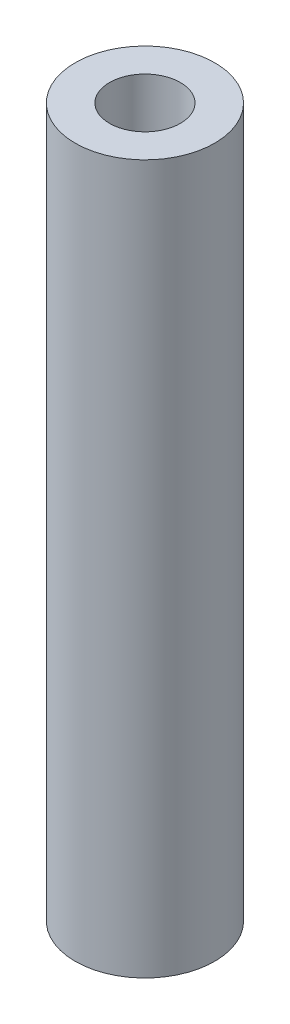
SolidWorks part; units mm, degrees
ref_plane "前视基准面" through (0, 0, 0) normal (0, 0, 1) x (1, 0, 0)
ref_plane "上视基准面" through (0, 0, 0) normal (0, 1, 0) x (1, 0, 0)
ref_plane "右视基准面" through (0, 0, 0) normal (1, 0, 0) x (0, 0, -1)
sketch "草图1" plane through (0, 0, 0) normal (0, 1, 0) x (1, 0, 0)
  circle A0 centre (0, 0) radius 2.54
  circle A1 centre (0, 0) radius 5
extrude "凸台-拉伸1" add sketch "草图1" along normal blind 50.8
